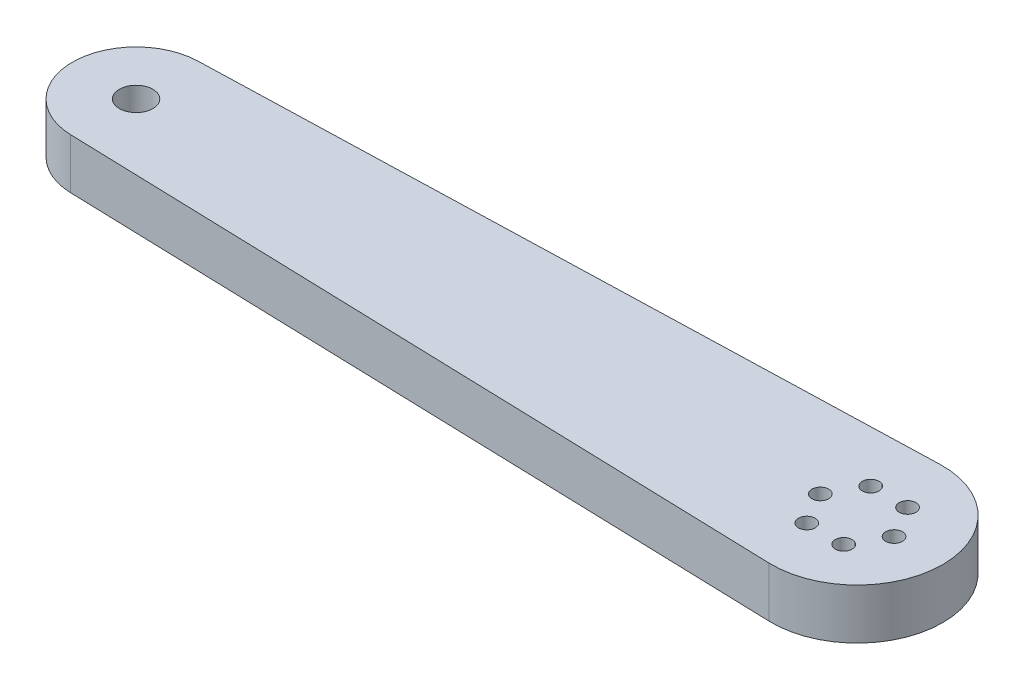
SolidWorks part; units mm, degrees
ref_plane "前视基准面" through (0, 0, 0) normal (0, 0, 1) x (1, 0, 0)
ref_plane "上视基准面" through (0, 0, 0) normal (0, 1, 0) x (1, 0, 0)
ref_plane "右视基准面" through (0, 0, 0) normal (1, 0, 0) x (0, 0, -1)
sketch "草图1" plane through (0, 0, 0) normal (0, 1, 0) x (1, 0, 0)
  line L0 (0, 0) -> (136.444, 0) construction
  line L1 (-0.5744, 18.9913) -> (214.2291, 25.4883)
  line L2 (-0.5744, -18.9913) -> (214.2291, -25.4883)
  line L4 (220.5, -9.5263) -> (226, 0) construction
  line L5 (226, 0) -> (220.5, 9.5263) construction
  line L6 (220.5, 9.5263) -> (209.5, 9.5263) construction
  line L7 (209.5, 9.5263) -> (204, 0) construction
  line L8 (204, 0) -> (209.5, -9.5263) construction
  line L9 (209.5, -9.5263) -> (220.5, -9.5263) construction
  circle A0 centre (0, 0) radius 5
  circle A1 centre (0, 0) radius 19 construction
  circle A3 centre (215, 0) radius 25.5 construction
  arc A4 (214.2291, 25.4883) -> (214.2291, -25.4883) centre (215, 0) cw
  arc A5 (-0.5744, 18.9913) -> (-0.5744, -18.9913) centre (0, 0) ccw
  circle A6 centre (215, 0) radius 11 construction
  circle A7 centre (215, 0) radius 9.5263 construction
  circle A8 centre (209.5, 9.5263) radius 2.5
  circle A9 centre (220.5, 9.5263) radius 2.5
  circle A10 centre (226, 0) radius 2.5
  circle A11 centre (220.5, -9.5263) radius 2.5
  circle A12 centre (209.5, -9.5263) radius 2.5
  circle A13 centre (204, 0) radius 2.5
  dimension "D1" = 10
  dimension "D2" = 38
  dimension "D3" = 22
  dimension "D5" = 51
  dimension "D6" = 5
  dimension "D4" = 215
extrude "凸台-拉伸1" add sketch "草图1" along normal blind 15
